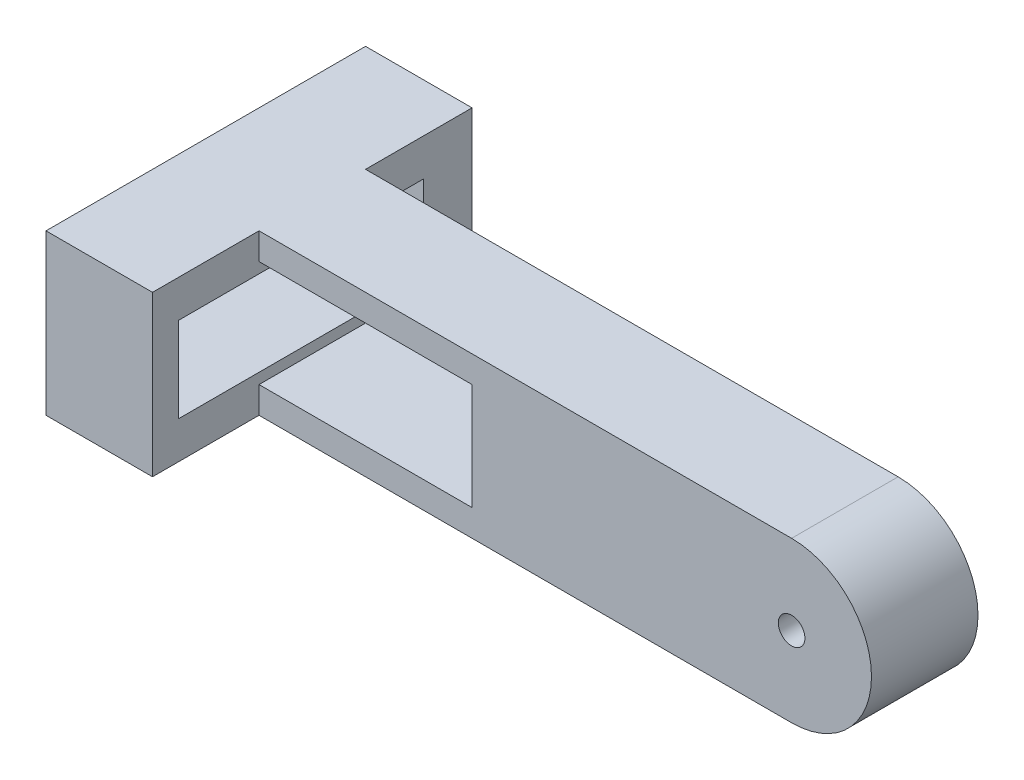
SolidWorks part; units mm, degrees
ref_plane "Front Plane" through (0, 0, 0) normal (0, 0, 1) x (1, 0, 0)
ref_plane "Top Plane" through (0, 0, 0) normal (0, 1, 0) x (1, 0, 0)
ref_plane "Right Plane" through (0, 0, 0) normal (1, 0, 0) x (0, 0, -1)
sketch "Sketch1" plane through (0, 0, 0) normal (0, 0, 1) x (1, 0, 0)
  line L1 (-76.2, -19.05) -> (76.2, -19.05)
  line L2 (-76.2, -19.05) -> (-76.2, 19.05)
  line L3 (-76.2, 19.05) -> (76.2, 19.05)
  line L4 (76.2, -19.05) -> (76.2, 19.05)
  line L5 (-76.2, -19.05) -> (76.2, 19.05) construction
  line L6 (-76.2, 19.05) -> (76.2, -19.05) construction
  circle A1 centre (76.2, 0) radius 19.05
  point P0 (0, 0)
  dimension "D1" = 38.1
  dimension "D2" = 152.4
extrude "Boss-Extrude1" add sketch "Sketch1" along normal blind 25.4
sketch "Sketch4" plane through (0, 0, 25.4) normal (0, 0, 1) x (1, 0, 0)
  line L0 (-76.2, -19.05) -> (76.2, -19.05) construction
  line L1 (-76.2, 19.05) -> (-50.8, 19.05)
  line L2 (-76.2, 19.05) -> (-76.2, -19.05)
  line L3 (-76.2, -19.05) -> (-50.8, -19.05)
  line L4 (-50.8, 19.05) -> (-50.8, -19.05)
  dimension "D1" = 25.4
extrude "Boss-Extrude3" add sketch "Sketch4" along normal blind 25.4
sketch "Sketch6" plane through (0, 0, 0) normal (0, 0, -1) x (-1, 0, 0)
  line L4 (76.2, -19.05) -> (76.2, 19.05)
  line L5 (50.8, -19.05) -> (76.2, -19.05)
  line L6 (50.8, 19.05) -> (50.8, -19.05)
  line L7 (76.2, 19.05) -> (50.8, 19.05)
  line L8 (76.2, -19.05) -> (76.2, 19.05)
  line L9 (50.8, -19.05) -> (76.2, -19.05)
  line L10 (50.8, 19.05) -> (50.8, -19.05)
  line L11 (76.2, 19.05) -> (50.8, 19.05)
  dimension "D1" = 0
extrude "Boss-Extrude4" add sketch "Sketch6" along normal blind 25.4
sketch "Sketch5" plane through (-76.2, 0, 0) normal (-1, 0, 0) x (0, 0, 1)
  line L0 (25.4, 19.05) -> (25.4, -19.05) construction
  line L3 (0, 0) -> (50.8, 0) construction
  line L4 (0, -19.05) -> (0, 19.05) construction
  line L5 (50.8, 19.05) -> (50.8, -19.05) construction
  line L6 (50.8, -19.05) -> (-25.4, -19.05) construction
  line L7 (50.8, 19.05) -> (-25.4, 19.05) construction
  line L8 (25.4, -19.05) -> (25.4, 19.05) construction
  circle A0 centre (25.4, 0) radius 6.985
  circle A1 centre (39.9001, 5) radius 1.905
  circle A2 centre (-9.0998, 5) radius 1.905
  circle A3 centre (-9.0998, -5) radius 1.905
  circle A4 centre (39.9001, -5) radius 1.905
  point P2 (21.2042, -25.4)
  point P5 (21.2751, 25.4)
  point P18 (0, 0)
  point P19 (0, 0)
  dimension "D1" = 13.97
  dimension "D2" = 3.81
  dimension "D3" = 48.9999
  dimension "D4" = 14.5001
  dimension "D5" = 10
extrude "Cut-Extrude1" cut sketch "Sketch5" against normal up to surface (25.4 mm away) up to face at (-50.8, 0, 38.1)
sketch "Sketch7" plane through (0, 0, 25.4) normal (0, 0, 1) x (1, 0, 0)
  line L0 (-50.8, 0) -> (0, 0) construction
  line L1 (-50.8, -19.05) -> (-50.8, 19.05) construction
  line L2 (-50.8, 6.985) -> (-50.8, 19.05) construction
  line L3 (0, -12.7) -> (-50.8, -12.7)
  line L4 (0, -12.7) -> (0, 12.7)
  line L5 (0, 12.7) -> (-50.8, 12.7)
  line L6 (-50.8, -12.7) -> (-50.8, 12.7)
  line L7 (0, -12.7) -> (-50.8, 12.7) construction
  line L8 (0, 12.7) -> (-50.8, -12.7) construction
  point P5 (-25.4, 0)
  dimension "D1" = 25.4
  dimension "D2" = 50.8
extrude "Cut-Extrude2" cut sketch "Sketch7" against normal up to surface (25.4 mm away) up to face at (17.4625, 0, 0)
sketch "Sketch8" plane through (-50.8, 0, 0) normal (1, 0, 0) x (0, 0, -1)
  line L0 (-15.4001, 10.16) -> (-15.4001, -10.16) construction
  line L1 (-35.7201, -10.16) -> (4.9199, -10.16)
  line L2 (-35.7201, -10.16) -> (-35.7201, 10.16)
  line L3 (-35.7201, 10.16) -> (4.9199, 10.16)
  line L4 (4.9199, -10.16) -> (4.9199, 10.16)
  line L5 (-35.7201, -10.16) -> (4.9199, 10.16) construction
  line L6 (-35.7201, 10.16) -> (4.9199, -10.16) construction
  line L7 (-50.8, 0) -> (25.4, 0) construction
  line L8 (-50.8, -19.05) -> (-50.8, 19.05) construction
  line L9 (25.4, 19.05) -> (25.4, -19.05) construction
  circle A0 centre (9.0998, -5) radius 1.905 construction
  circle A1 centre (-39.9001, -5) radius 1.905 construction
  point P0 (-15.4001, 0)
  point P17 (-15.4001, 0.7547)
  dimension "D1" = 40.64
  dimension "D2" = 20.32
extrude "Cut-Extrude3" cut sketch "Sketch8" against normal offset from surface (23.4 mm away) 2 up to face at (-76.2, -5, 37.9951)
sketch "Sketch9" plane through (-50.8, 0, 0) normal (1, 0, 0) x (0, 0, -1)
  line L0 (-15.4001, 10.16) -> (-15.4001, -10.16) construction
  line L1 (4.9199, 10.16) -> (-35.7201, 10.16) construction
  line L2 (-35.7201, -10.16) -> (4.9199, -10.16) construction
  line L3 (-35.7201, 10.16) -> (-35.7201, -10.16) construction
  line L4 (-35.7201, 10.16) -> (-44.6101, 10.16)
  line L5 (-35.7201, 10.16) -> (-35.7201, -10.16)
  line L6 (-35.7201, -10.16) -> (-44.6101, -10.16)
  line L7 (-44.6101, 10.16) -> (-44.6101, -10.16)
  line L8 (4.9199, -10.16) -> (13.8099, -10.16)
  line L9 (13.8099, 10.16) -> (13.8099, -10.16)
  line L10 (4.9199, 10.16) -> (13.8099, 10.16)
  line L11 (4.9199, 10.16) -> (4.9199, -10.16)
  point P11 (-35.7201, -10.16)
  dimension "D1" = 8.89
extrude "Cut-Extrude4" cut sketch "Sketch9" against normal offset from surface (14.8001 mm away) 10.5999 up to face at (-76.2, -5, 37.9951)
sketch "Sketch10" plane through (-65.6001, 0, 0) normal (1, 0, 0) x (0, 0, -1)
  line L0 (-44.6101, 0) -> (13.8099, 0) construction
  line L1 (-44.6101, 10.16) -> (-44.6101, -10.16) construction
  line L2 (13.8099, -10.16) -> (13.8099, 10.16) construction
  line L3 (-15.4001, 10.16) -> (-15.4001, -10.16) construction
  line L4 (13.8099, 10.16) -> (-44.6101, 10.16) construction
  line L5 (-35.7201, -10.16) -> (4.9199, -10.16) construction
  line L6 (-44.6101, 10.16) -> (-44.6101, -10.16) construction
  line L7 (-35.7201, -1.27) -> (-44.6101, -1.27)
  line L8 (-35.7201, -1.27) -> (-35.7201, 1.27)
  line L9 (-35.7201, 1.27) -> (-44.6101, 1.27)
  line L10 (-44.6101, -1.27) -> (-44.6101, 1.27)
  line L11 (-35.7201, -1.27) -> (-44.6101, 1.27) construction
  line L12 (-35.7201, 1.27) -> (-44.6101, -1.27) construction
  line L13 (-35.7201, -10.16) -> (-35.7201, 10.16) construction
  line L14 (4.9199, 1.27) -> (13.8099, 1.27)
  line L15 (13.8099, -1.27) -> (13.8099, 1.27)
  line L16 (4.9199, -1.27) -> (13.8099, -1.27)
  line L17 (4.9199, -1.27) -> (4.9199, 1.27)
  point P12 (-40.1651, 0)
  point P19 (-35.7201, 2.3032)
  dimension "D1" = 2.54
extrude "Cut-Extrude5" cut sketch "Sketch10" against normal up to surface (8.5999 mm away) up to face at (-74.2, 0, 15.4001)
sketch "Sketch11" plane through (0, 0, 25.4) normal (0, 0, 1) x (1, 0, 0)
  circle A0 centre (76.2, 0) radius 3.175
  arc A1 (76.2, -19.05) -> (76.2, 19.05) centre (76.2, 0) ccw construction
  dimension "D1" = 6.35
extrude "Cut-Extrude6" cut sketch "Sketch11" against normal through all
